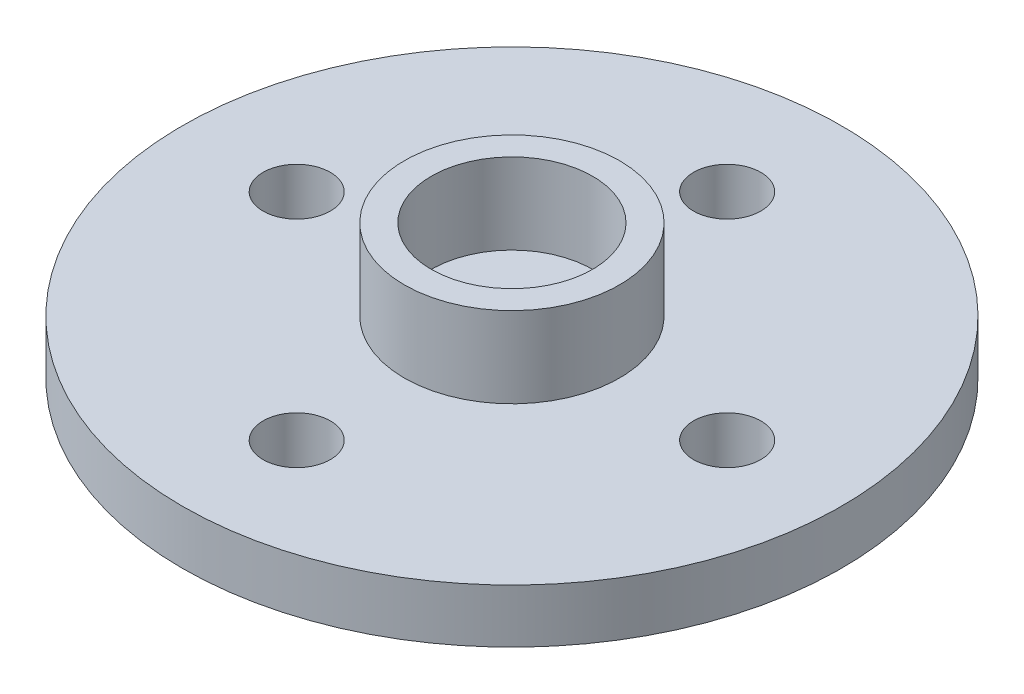
SolidWorks part; units mm, degrees
ref_plane "前视基准面" through (0, 0, 0) normal (0, 0, 1) x (1, 0, 0)
ref_plane "上视基准面" through (0, 0, 0) normal (0, 1, 0) x (1, 0, 0)
ref_plane "右视基准面" through (0, 0, 0) normal (1, 0, 0) x (0, 0, -1)
sketch "草图1" plane through (0, 0, 0) normal (0, 1, 0) x (1, 0, 0)
  circle A0 centre (0, 0) radius 12.25
  dimension "D1" = 24.5
extrude "凸台-拉伸1" add sketch "草图1" along normal blind 2
sketch "草图2" plane through (0, 2, 0) normal (0, 1, 0) x (1, 0, 0)
  circle A0 centre (0, 0) radius 4
  dimension "D1" = 8
extrude "凸台-拉伸2" add sketch "草图2" along normal blind 3
sketch "草图3" plane through (0, 2, 0) normal (0, 1, 0) x (1, 0, 0)
  circle A0 centre (-8, 0) radius 1.25
  circle A1 centre (0, 8) radius 1.25
  circle A2 centre (8, 0) radius 1.25
  circle A3 centre (0, -8) radius 1.25
  point P11 (0, 0)
  dimension "D2" = 16
  dimension "D3" = 2.5
  dimension "D1" = 4
extrude "切除-拉伸1" cut sketch "草图3" against normal blind 3
sketch "草图4" plane through (0, 5, 0) normal (0, 1, 0) x (1, 0, 0)
  circle A0 centre (0, 0) radius 3
  dimension "D1" = 6
extrude "切除-拉伸2" cut sketch "草图4" against normal blind 3
